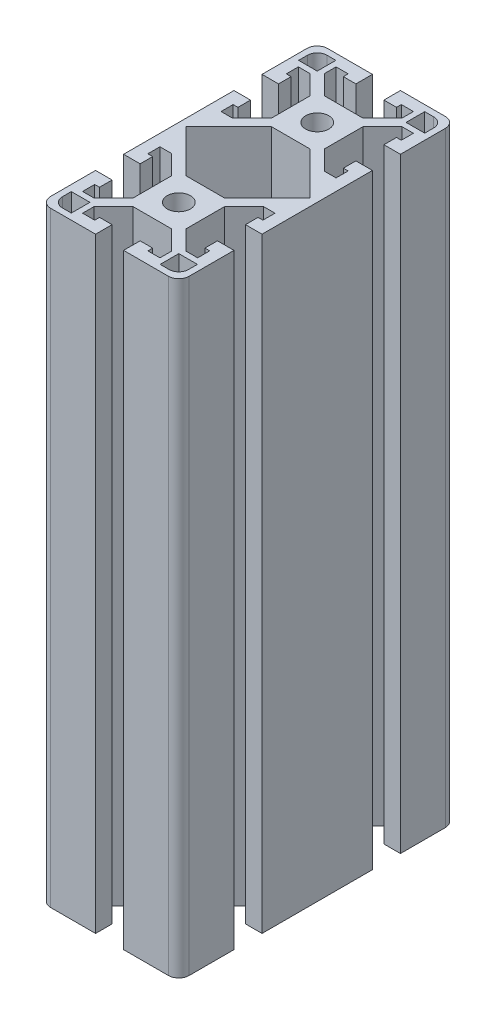
SolidWorks part; units mm, degrees
material "6063-T6"
ref_plane "Front Plane" through (0, 0, 0) normal (0, 0, 1) x (1, 0, 0)
ref_plane "Top Plane" through (0, 0, 0) normal (0, 1, 0) x (1, 0, 0)
ref_plane "Right Plane" through (0, 0, 0) normal (1, 0, 0) x (0, 0, -1)
sketch "Sketch1" plane through (0, 0, 0) normal (0, 0, 1) x (1, 0, 0)
  line L0 (0, 0) -> (0, 175)
  dimension "D1" = 175
other "40 series TS40-80LM-650037(1)"
ref_plane "Plane1" through (0, 0, 0) normal (0, 1, 0) x (-1, 0, 0)
sketch "Sketch2" plane through (0, 0, 0) normal (0, 1, 0) x (-1, 0, 0)
  line L2 (0, -27.681) -> (-5.5257, -27.681)
  line L3 (-5.5257, -27.681) -> (-11.176, -33.3313)
  line L4 (-7.6835, -36.6218) -> (-11.176, -36.6218)
  line L5 (-20, -37) -> (-20, -24.0488)
  line L6 (-4.0488, -40) -> (-17, -40)
  line L7 (-7.681, -20) -> (-7.681, -25.5257)
  line L8 (-7.681, -25.5257) -> (-13.3313, -31.176)
  line L9 (-16.6218, -31.176) -> (-16.6218, -27.6835)
  line L10 (-7.681, -14.4743) -> (-13.3313, -8.824)
  line L11 (-13.3313, -8.824) -> (-16.6218, -8.824)
  line L12 (-20, -24.0488) -> (-15.2248, -24.0488)
  line L13 (-20, 15.9512) -> (-20, -15.9512)
  line L14 (-5.5257, 12.319) -> (-17.8447, 0)
  line L15 (-5.5257, -12.319) -> (-17.8447, 0)
  line L16 (-7.681, -20) -> (-7.681, -14.4743)
  line L17 (-5.5257, -12.319) -> (0, -12.319)
  line L18 (7.681, -20) -> (7.681, -14.4743)
  line L19 (5.5257, -12.319) -> (17.8447, 0)
  line L20 (20, 15.9512) -> (15.2248, 15.9512)
  line L21 (4.0488, -35.2248) -> (7.6835, -35.2248)
  line L22 (7.681, 14.4743) -> (13.3313, 8.824)
  line L23 (7.6835, -36.6218) -> (7.6835, -35.2248)
  line L24 (4.0488, -35.2248) -> (4.0488, -40)
  line L25 (7.6835, -36.6218) -> (11.176, -36.6218)
  line L26 (11.176, -33.3313) -> (11.176, -36.6218)
  line L27 (7.681, -20) -> (7.681, -25.5257)
  line L28 (4.0488, -40) -> (17, -40)
  line L29 (20, -37) -> (20, -24.0488)
  line L30 (5.5257, -27.681) -> (11.176, -33.3313)
  line L31 (7.681, -25.5257) -> (13.3313, -31.176)
  line L32 (0, -12.319) -> (5.5257, -12.319)
  line L33 (0, -27.681) -> (5.5257, -27.681)
  line L35 (13.3313, 8.824) -> (16.6218, 8.824)
  line L36 (0, 12.319) -> (5.5257, 12.319)
  line L37 (-5.5257, 12.319) -> (0, 12.319)
  line L38 (16.6218, 8.824) -> (16.6218, 12.3165)
  line L39 (15.2248, 15.9512) -> (15.2248, 12.3165)
  line L40 (16.6218, 12.3165) -> (15.2248, 12.3165)
  line L41 (20, 24.0488) -> (15.2248, 24.0488)
  line L42 (0, 27.681) -> (5.5257, 27.681)
  line L43 (-4.0488, 40) -> (-17, 40)
  line L44 (-20, 37) -> (-20, 24.0488)
  line L45 (4.0488, 35.2248) -> (4.0488, 40)
  line L46 (16.6218, 31.176) -> (16.6218, 27.6835)
  line L47 (7.681, 20) -> (7.681, 25.5257)
  line L48 (13.3313, 31.176) -> (16.6218, 31.176)
  line L49 (15.2248, 24.0488) -> (15.2248, 27.6835)
  line L50 (7.681, 20) -> (7.681, 14.4743)
  line L51 (-7.681, 25.5257) -> (-7.681, 14.4743)
  line L52 (16.6218, 27.6835) -> (15.2248, 27.6835)
  line L53 (12.8372, 38.222) -> (12.8372, 32.8372)
  line L54 (20, 37) -> (20, 24.0488)
  line L55 (4.0488, 40) -> (17, 40)
  line L56 (12.8372, 38.222) -> (15.428, 38.222)
  line L57 (18.222, 35.428) -> (18.222, 32.8372)
  line L58 (12.8372, 32.8372) -> (18.222, 32.8372)
  line L59 (0, 27.681) -> (-5.5257, 27.681)
  line L60 (-4.0488, -35.2248) -> (-4.0488, -40)
  line L61 (-16.6218, -8.824) -> (-16.6218, -12.3165)
  line L62 (7.681, -14.4743) -> (13.3313, -8.824)
  line L63 (12.8372, -32.8372) -> (18.222, -32.8372)
  line L64 (20, 15.9512) -> (20, -15.9512)
  line L65 (7.681, 25.5257) -> (13.3313, 31.176)
  line L66 (5.5257, 27.681) -> (11.176, 33.3313)
  line L67 (5.5257, 12.319) -> (17.8447, 0)
  line L68 (-13.3313, -31.176) -> (-16.6218, -31.176)
  line L69 (-11.176, -33.3313) -> (-11.176, -36.6218)
  line L70 (-15.2248, -15.9512) -> (-15.2248, -12.3165)
  line L71 (-12.8372, -38.222) -> (-12.8372, -32.8372)
  line L72 (-12.8372, -38.222) -> (-15.428, -38.222)
  line L73 (-15.2248, -24.0488) -> (-15.2248, -27.6835)
  line L74 (-16.6218, -27.6835) -> (-15.2248, -27.6835)
  line L75 (-18.222, -35.428) -> (-18.222, -32.8372)
  line L76 (-12.8372, -32.8372) -> (-18.222, -32.8372)
  line L77 (-7.6835, -36.6218) -> (-7.6835, -35.2248)
  line L78 (-4.0488, -35.2248) -> (-7.6835, -35.2248)
  line L79 (-20, -15.9512) -> (-15.2248, -15.9512)
  line L80 (-16.6218, -12.3165) -> (-15.2248, -12.3165)
  line L81 (18.222, -35.428) -> (18.222, -32.8372)
  line L82 (12.8372, -38.222) -> (15.428, -38.222)
  line L83 (12.8372, -38.222) -> (12.8372, -32.8372)
  line L84 (16.6218, -12.3165) -> (15.2248, -12.3165)
  line L85 (20, -15.9512) -> (15.2248, -15.9512)
  line L86 (16.6218, -27.6835) -> (15.2248, -27.6835)
  line L87 (15.2248, -24.0488) -> (15.2248, -27.6835)
  line L88 (15.2248, -15.9512) -> (15.2248, -12.3165)
  line L89 (13.3313, -31.176) -> (16.6218, -31.176)
  line L90 (16.6218, -8.824) -> (16.6218, -12.3165)
  line L91 (20, -24.0488) -> (15.2248, -24.0488)
  line L92 (13.3313, -8.824) -> (16.6218, -8.824)
  line L93 (16.6218, -31.176) -> (16.6218, -27.6835)
  line L94 (11.176, 33.3313) -> (11.176, 36.6218)
  line L95 (7.6835, 36.6218) -> (11.176, 36.6218)
  line L96 (7.6835, 36.6218) -> (7.6835, 35.2248)
  line L97 (4.0488, 35.2248) -> (7.6835, 35.2248)
  line L98 (-4.0488, 35.2248) -> (-4.0488, 40)
  line L99 (-4.0488, 35.2248) -> (-7.6835, 35.2248)
  line L100 (-7.6835, 36.6218) -> (-7.6835, 35.2248)
  line L101 (-7.6835, 36.6218) -> (-11.176, 36.6218)
  line L102 (-11.176, 33.3313) -> (-11.176, 36.6218)
  line L103 (-5.5257, 27.681) -> (-11.176, 33.3313)
  line L104 (-18.222, 35.428) -> (-18.222, 32.8372)
  line L105 (-12.8372, 32.8372) -> (-18.222, 32.8372)
  line L106 (-7.681, 25.5257) -> (-13.3313, 31.176)
  line L107 (-13.3313, 31.176) -> (-16.6218, 31.176)
  line L108 (-16.6218, 31.176) -> (-16.6218, 27.6835)
  line L109 (-7.681, 14.4743) -> (-13.3313, 8.824)
  line L110 (-16.6218, 12.3165) -> (-15.2248, 12.3165)
  line L111 (-20, 15.9512) -> (-15.2248, 15.9512)
  line L112 (-15.2248, 15.9512) -> (-15.2248, 12.3165)
  line L113 (-16.6218, 8.824) -> (-16.6218, 12.3165)
  line L114 (-13.3313, 8.824) -> (-16.6218, 8.824)
  line L115 (-16.6218, 27.6835) -> (-15.2248, 27.6835)
  line L116 (-15.2248, 24.0488) -> (-15.2248, 27.6835)
  line L117 (-20, 24.0488) -> (-15.2248, 24.0488)
  line L118 (-12.8372, 38.222) -> (-15.428, 38.222)
  line L119 (-12.8372, 38.222) -> (-12.8372, 32.8372)
  arc A0 (-20, -37) -> (-17, -40) centre (-17, -37) ccw
  arc A1 (-20, 37) -> (-17, 40) centre (-17, 37) cw
  arc A2 (20, 37) -> (17, 40) centre (17, 37) ccw
  arc A3 (-15.428, -38.222) -> (-18.222, -35.428) centre (-15.428, -35.428) cw
  arc A4 (15.428, -38.222) -> (18.222, -35.428) centre (15.428, -35.428) ccw
  arc A5 (15.428, 38.222) -> (18.222, 35.428) centre (15.428, 35.428) cw
  arc A6 (-15.428, 38.222) -> (-18.222, 35.428) centre (-15.428, 35.428) ccw
  arc A7 (20, -37) -> (17, -40) centre (17, -37) cw
  circle A8 centre (0, -20) radius 3.35
  circle A9 centre (0, 20) radius 3.35
  point P1 (-20, 20)
  point P3 (-20, 40)
  point P34 (-20, 0)
  point P51 (20, 0)
  point P76 (0, 40)
  point P77 (20, 40)
  point P143 (20, 20)
  point P144 (20, -20)
  point P145 (-20, -20)
  point P146 (-20, -40)
  point P147 (0, -40)
  point P148 (20, -40)
  point P149 (0, 0)
  dimension "D1" = 6.7
